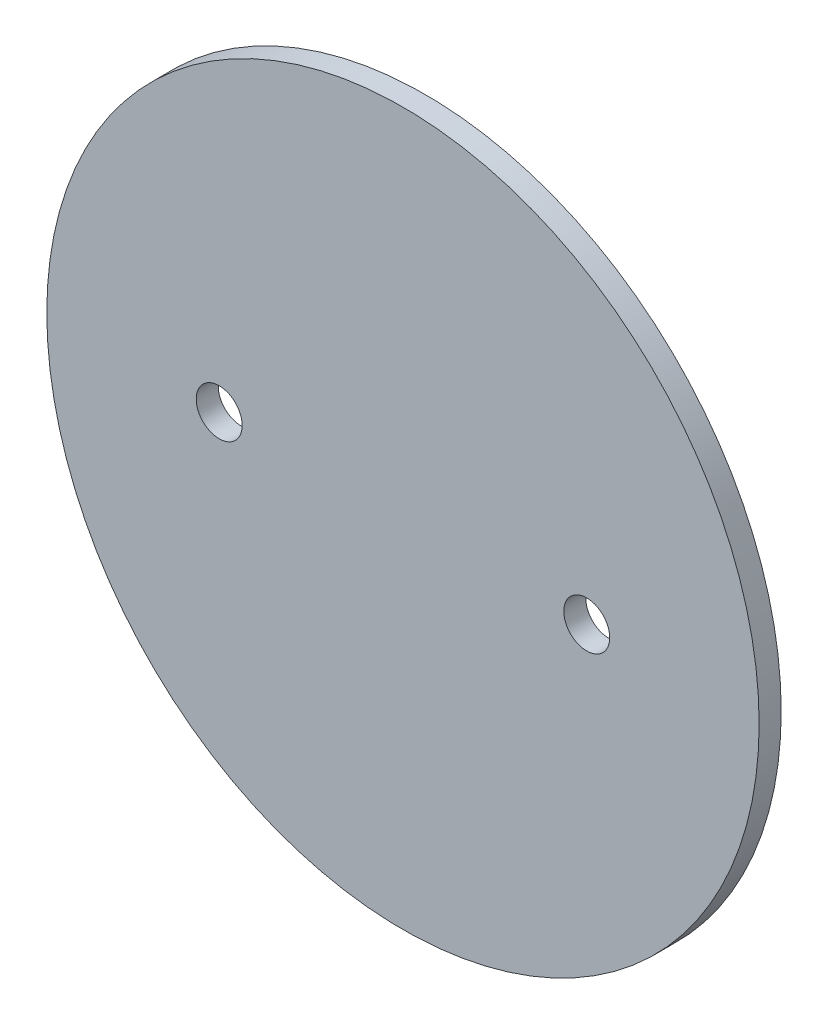
SolidWorks part; units mm, degrees
ref_plane "Front Plane" through (0, 0, 0) normal (0, 0, 1) x (1, 0, 0)
ref_plane "Top Plane" through (0, 0, 0) normal (0, 1, 0) x (1, 0, 0)
ref_plane "Right Plane" through (0, 0, 0) normal (1, 0, 0) x (0, 0, -1)
sketch "Sketch1" plane through (0, 0, 0) normal (0, 0, 1) x (1, 0, 0)
  line L0 (0, 0) -> (0, 64.0846) construction
  circle A0 centre (0, 0) radius 96.9
  circle A1 centre (-50, 0) radius 6.25
  circle A2 centre (50, 0) radius 6.25
  point P7 (0, 0)
  dimension "D1" = 193.8
  dimension "D3" = 12.5
  dimension "D2" = 100
extrude "Boss-Extrude1" add sketch "Sketch1" along normal mid plane 6
